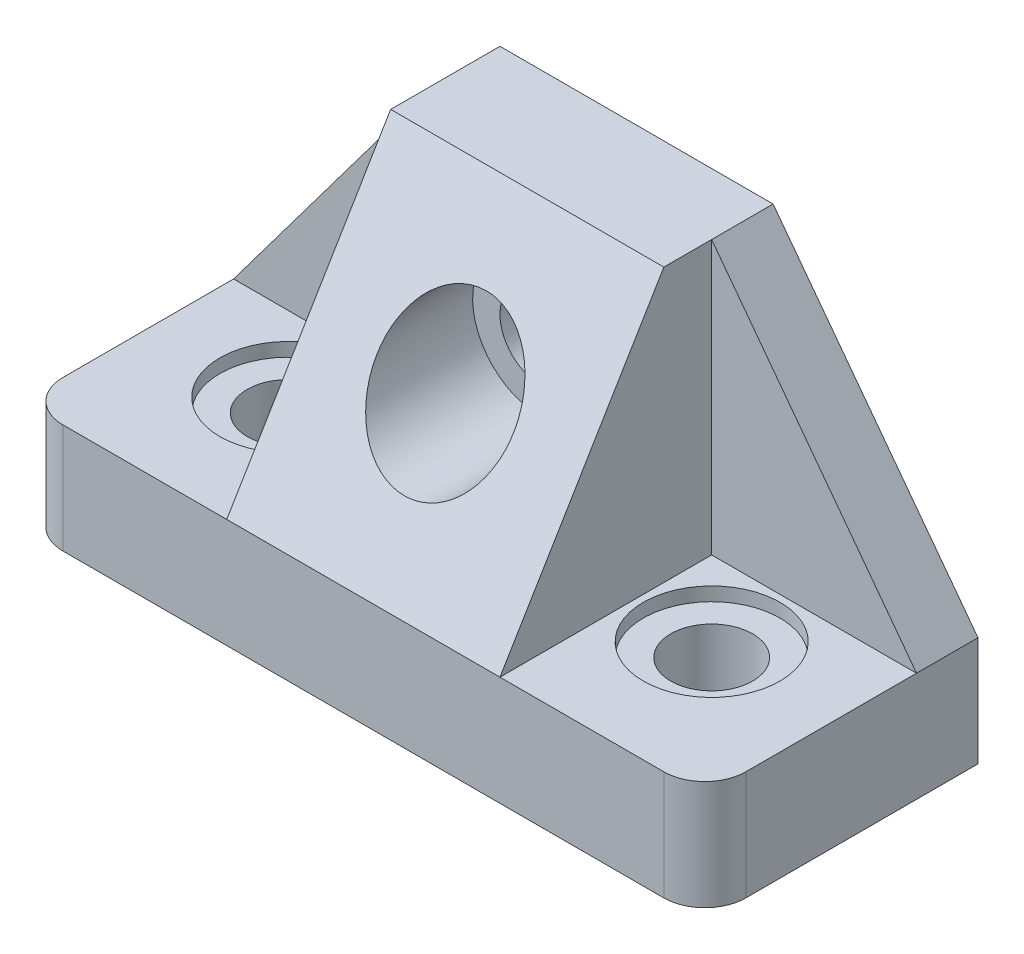
SolidWorks part; units mm, degrees
ref_plane "Front Plane" through (0, 0, 0) normal (0, 0, 1) x (1, 0, 0)
ref_plane "Top Plane" through (0, 0, 0) normal (0, 1, 0) x (1, 0, 0)
ref_plane "Right Plane" through (0, 0, 0) normal (1, 0, 0) x (0, 0, -1)
sketch "Sketch1" plane through (0, 0, 0) normal (0, 1, 0) x (1, 0, 0)
  line L1 (-25, 10) -> (25, 10)
  line L2 (-25, 10) -> (-25, -10)
  line L3 (-25, -10) -> (25, -10)
  line L4 (25, 10) -> (25, -10)
  line L5 (-25, 10) -> (25, -10) construction
  line L6 (-25, -10) -> (25, 10) construction
  point P0 (0, 0)
extrude "Boss-Extrude1" add sketch "Sketch1" along normal blind 8
sketch "Sketch2" plane through (0, 8, 0) normal (0, 1, 0) x (1, 0, 0)
  line L0 (25, 10) -> (-25, 10) construction
  line L1 (-10, 10) -> (10, 10)
  line L2 (-10, 10) -> (-10, 2)
  line L3 (-10, 2) -> (10, 2)
  line L4 (10, 10) -> (10, 2)
  line L5 (-10, 10) -> (10, 2) construction
  line L6 (-10, 2) -> (10, 10) construction
  dimension "D1" = 20
  dimension "D2" = 8
extrude "Boss-Extrude2" add sketch "Sketch2" along normal blind 20
sketch "Sketch3" plane through (0, 0, 0) normal (1, 0, 0) x (0, 0, -1)
  line L0 (2, 28) -> (-10, 8)
rib "Rib3" sketch "Sketch3" sketch "Sketch3" thickness 20 extrusion direction parallel to sketch draft on no parameters "D1"=20
sketch "Sketch7" plane through (0, 8, 0) normal (0, 1, 0) x (1, 0, 0)
  circle A0 centre (-15.5, 0) radius 5
sketch "Sketch9" plane through (0, 0, 0) normal (0, 0, 1) x (1, 0, 0)
  circle A0 centre (0, 18) radius 5
extrude "Cut-Extrude3" cut sketch "Sketch9" along normal blind 12 from offset 3 offset against normal yes
sketch "Sketch10" plane through (0, 0, -3) normal (0, 0, 1) x (1, 0, 0)
  circle A0 centre (0, 18) radius 3
extrude "Cut-Extrude4" cut sketch "Sketch10" against normal blind 7
sketch "Sketch12" plane through (0, 0, -10) normal (0, 0, -1) x (-1, 0, 0)
  line L0 (10, 28) -> (25, 8)
rib "Rib4" sketch "Sketch12" sketch "Sketch12" thickness 4.5 extrusion direction parallel to sketch draft on no parameters "D1"=4.5
sketch "Sketch13" plane through (0, 0, -10) normal (0, 0, -1) x (-1, 0, 0)
  line L0 (-10, 28) -> (-25, 8)
rib "Rib7" sketch "Sketch13" sketch "Sketch13" thickness 4.5 extrusion direction parallel to sketch draft on no parameters "D1"=4.5
extrude "Cut-Extrude5" cut sketch "Sketch7" against normal blind 1
sketch "Sketch14" plane through (0, 7, 0) normal (0, 1, 0) x (1, 0, 0)
  circle A0 centre (-15.5, 0) radius 3
extrude "Cut-Extrude6" cut sketch "Sketch14" against normal blind 7
pattern_linear "LPattern1" count 2 spacing 31 along (1, 0, 0) of "Cut-Extrude5", "Cut-Extrude6"
sketch "Sketch15" plane through (0, 0, 0) normal (0, -1, 0) x (1, 0, 0)
  line L1 (-2.9, -10) -> (2.9, -10)
  line L2 (-2.9, -10) -> (-2.9, -13)
  line L3 (-2.9, -13) -> (2.9, -13)
  line L4 (2.9, -10) -> (2.9, -13)
  line L5 (-2.9, -10) -> (2.9, -13) construction
  line L6 (-2.9, -13) -> (2.9, -10) construction
  line L7 (25, -10) -> (-25, -10) construction
  point P0 (0, -11.5)
  point P7 (0, -10)
  dimension "D1" = 5.8
  dimension "D2" = 3
extrude "Boss-Extrude3" add sketch "Sketch15" against normal blind 10
fillet "Fillet1" radius 3 1 edges at (-25, 4, 10)
fillet "Fillet2" radius 3 1 edges at (25, 4, 10)
